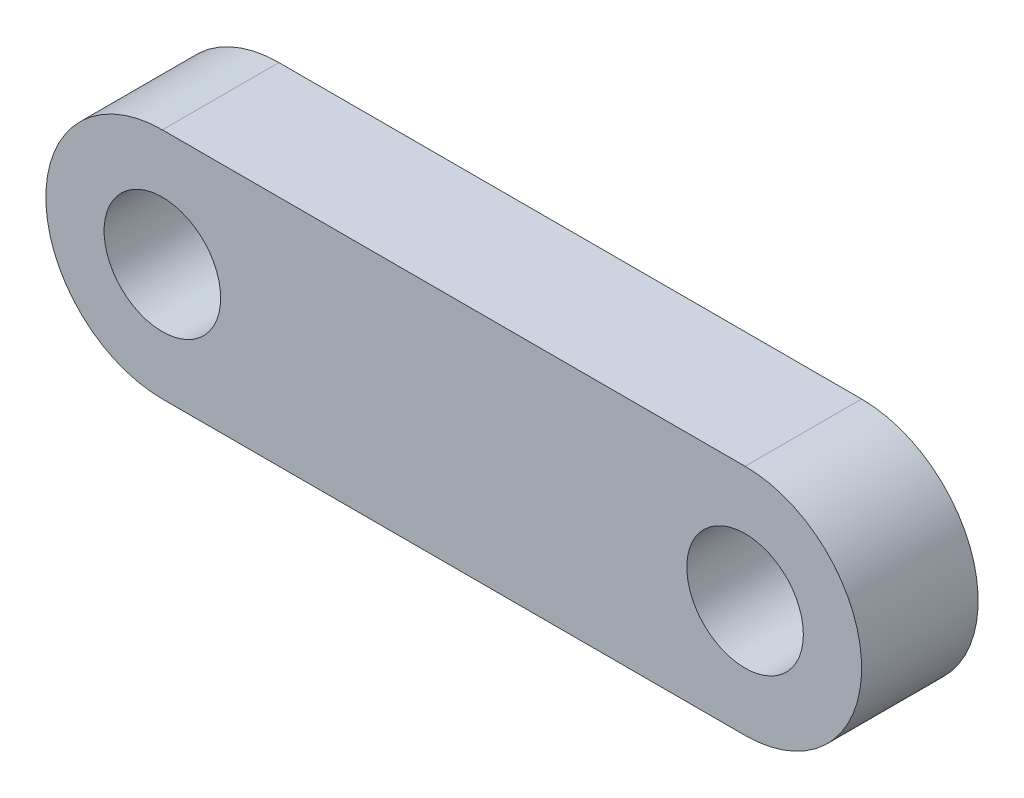
SolidWorks part; units mm, degrees
ref_plane "前基準面" through (0, 0, 0) normal (0, 0, 1) x (1, 0, 0)
ref_plane "上基準面" through (0, 0, 0) normal (0, 1, 0) x (1, 0, 0)
ref_plane "右基準面" through (0, 0, 0) normal (1, 0, 0) x (0, 0, -1)
sketch "草圖1" plane through (0, 0, 0) normal (0, 0, 1) x (1, 0, 0)
  line L0 (-5, 2.0003) -> (5, 2.0003)
  line L1 (-5, -1.9997) -> (5, -1.9997)
  arc A0 (-5, 2.0003) -> (-5, -1.9997) centre (-5, 0.0003) ccw
  arc A1 (5, -1.9997) -> (5, 2.0003) centre (5, 0.0003) ccw
  circle A2 centre (-5, 0.0003) radius 1
  circle A3 centre (5, 0.0003) radius 1
  dimension "D1" = 10
  dimension "D2" = 2
  dimension "D3" = 2
  dimension "D4" = 2
  dimension "D5" = 5
extrude "填料-伸長1" add sketch "草圖1" along normal blind 2
